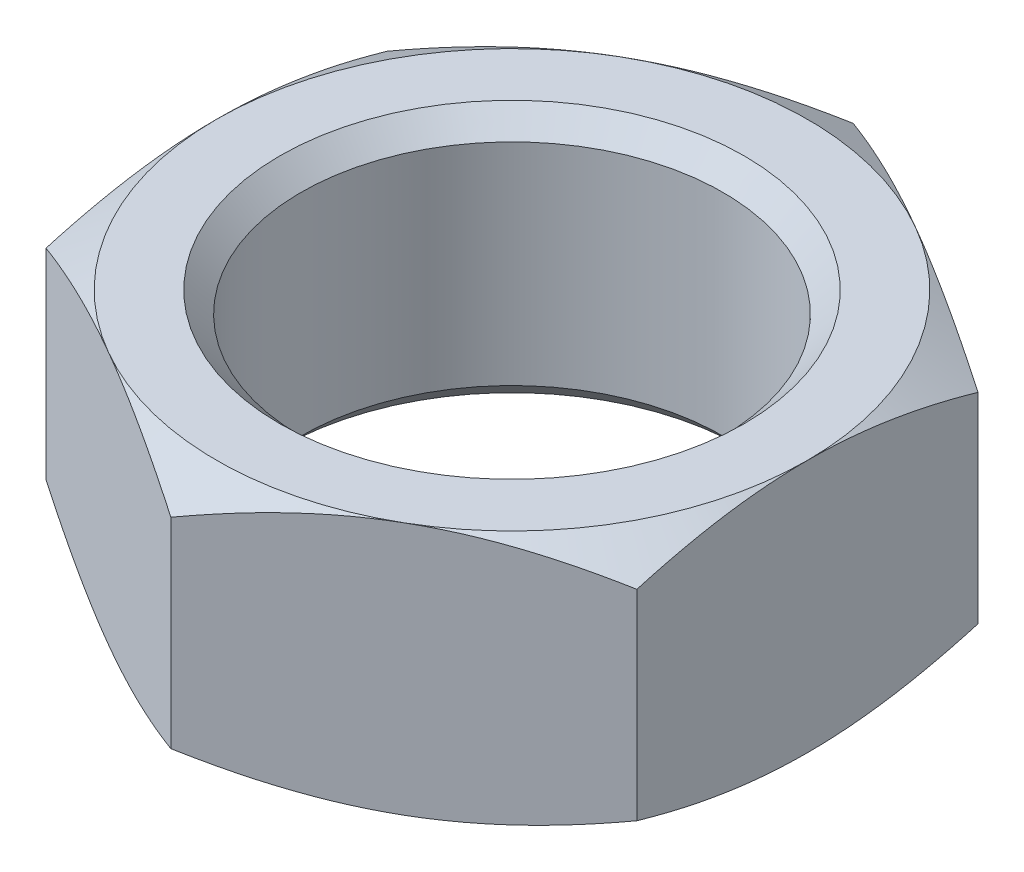
SolidWorks part; units mm, degrees
ref_plane "Front Plane" through (0, 0, 0) normal (0, 0, 1) x (1, 0, 0)
ref_plane "Top Plane" through (0, 0, 0) normal (0, 1, 0) x (1, 0, 0)
ref_plane "Right Plane" through (0, 0, 0) normal (1, 0, 0) x (0, 0, -1)
sketch "Sketch3" plane through (0, 0, 0) normal (0, 1, 0) x (1, 0, 0)
  line L1 (0, 16.1658) -> (-14, 8.0829)
  line L2 (-14, 8.0829) -> (-14, -8.0829)
  line L3 (-14, -8.0829) -> (0, -16.1658)
  line L4 (0, -16.1658) -> (14, -8.0829)
  line L5 (14, -8.0829) -> (14, 8.0829)
  line L6 (14, 8.0829) -> (0, 16.1658)
  circle A0 centre (0, 0) radius 14 construction
extrude "Boss-Extrude1" add sketch "Sketch3" along normal mid plane 12
sketch "Sketch5" plane through (0, 6, 0) normal (0, 1, 0) x (1, 0, 0)
  line L0 (14, 8.0829) -> (0, 16.1658) construction
  circle A0 centre (0, 0) radius 14
extrude "Cut-Extrude1" cut sketch "Sketch5" against normal blind 12 draft 60 flip side to cut
mirror "Mirror1" about plane through (0, 0, 0) normal (0, 1, 0) of "Cut-Extrude1"
sketch "Sketch6" plane through (0, 6, 0) normal (0, 1, 0) x (1, 0, 0)
  circle A0 centre (0, 0) radius 10
extrude "Cut-Extrude2" cut sketch "Sketch6" against normal through all
chamfer "Chamfer1" distance 1 angle 45 1 edges at (0, 6, 10)
chamfer "Chamfer2" distance 1 angle 45 1 edges at (0, -6, 10)
